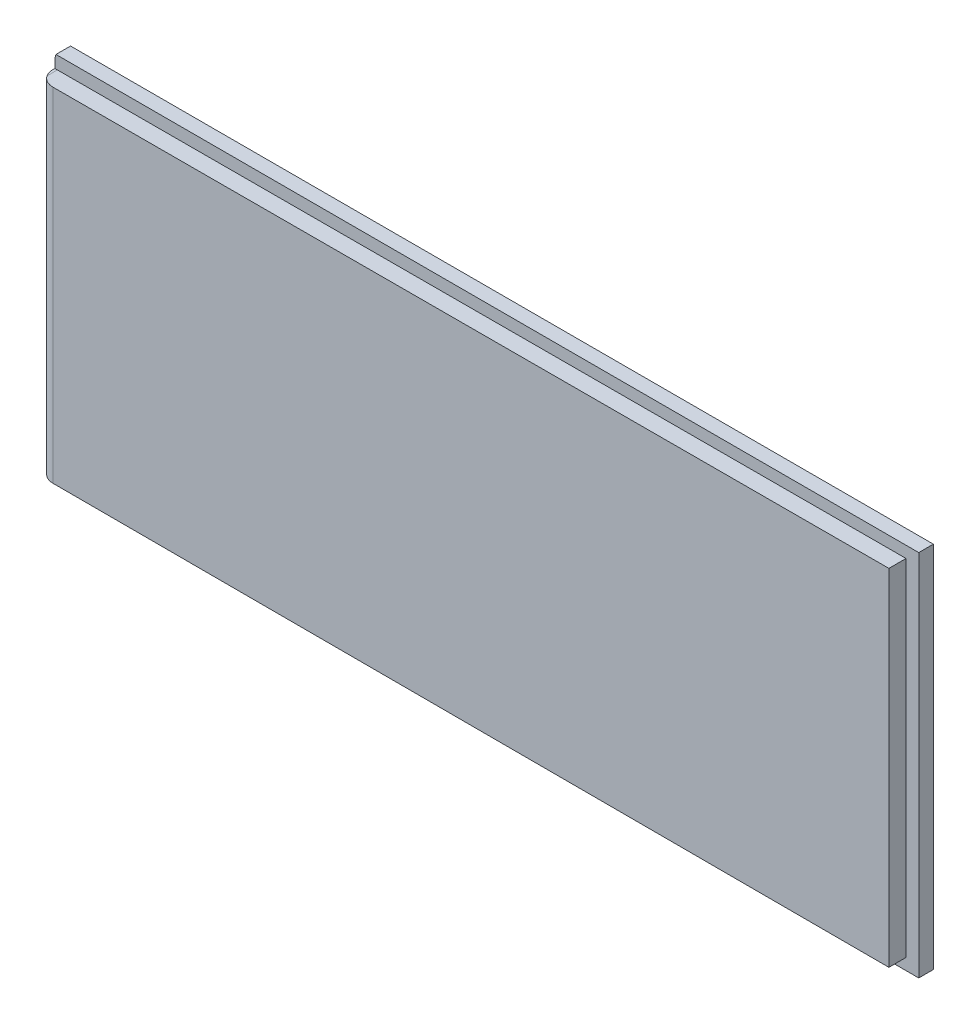
SolidWorks part; units mm, degrees
ref_plane "前视基准面" through (0, 0, 0) normal (0, 0, 1) x (1, 0, 0)
ref_plane "上视基准面" through (0, 0, 0) normal (0, 1, 0) x (1, 0, 0)
ref_plane "右视基准面" through (0, 0, 0) normal (1, 0, 0) x (0, 0, -1)
sketch "草图1" plane through (0, 0, -0.6466) normal (0, 0, 1) x (1, 0, 0)
  line L7 (-91.5, 11.1) -> (-91.5, -11.1) construction
  line L8 (-91.3, 11.1) -> (-91.3, -11.1)
  line L9 (-91.3, -11.1) -> (-91.3, -14)
  line L10 (-91.1125, -14.8) -> (-22.7, -14.8)
  line L11 (-22.7, -14.8) -> (-22.7, 14.8)
  line L12 (-74.5, 11.1) -> (-74.5, 14.3)
  line L13 (-74.5, 14.3) -> (-23.3, 14.3)
  line L14 (-22.7, 14.8) -> (-91.1125, 14.8)
  line L15 (-23.3, 14.3) -> (-23.3, -14.3)
  line L16 (-74.5, -14.3) -> (-74.5, -11.1)
  line L17 (-75.5, -10.1) -> (-90.5, -10.1)
  line L18 (-91.5, -11.1) -> (-91.5, -14)
  line L19 (-91.2321, -15) -> (-22.5, -15)
  line L20 (-22.5, -15) -> (-22.5, 15)
  line L21 (-22.5, 15) -> (-91.2321, 15)
  line L22 (-91.5, 14) -> (-91.5, 11.1)
  line L23 (-90.5, 10.1) -> (-75.5, 10.1)
  line L30 (-91.5, -11.1) -> (-91.5, -14) construction
  line L31 (-91.2321, -15) -> (-22.5, -15) construction
  line L32 (-22.5, -15) -> (-22.5, 15) construction
  line L33 (-22.5, 15) -> (-91.2321, 15) construction
  line L34 (-91.5, 14) -> (-91.5, 11.1) construction
  line L36 (-91.3, 14) -> (-91.3, 11.1)
  line L55 (-23.3, -14.3) -> (-74.5, -14.3)
  arc A2 (-91.3, -14) -> (-91.1125, -14.8) centre (-89.5, -14) ccw
  arc A3 (-91.1125, 14.8) -> (-91.3, 14) centre (-89.5, 14) ccw
  arc A4 (-75.5, 10.1) -> (-74.5, 11.1) centre (-75.5, 11.1) ccw
  arc A5 (-74.5, -11.1) -> (-75.5, -10.1) centre (-75.5, -11.1) ccw
  arc A6 (-91.5, -14) -> (-91.2321, -15) centre (-89.5, -14) ccw
  arc A7 (-91.2321, 15) -> (-91.5, 14) centre (-89.5, 14) ccw
  arc A10 (-91.5, -14) -> (-91.2321, -15) centre (-89.5, -14) ccw construction
  arc A11 (-91.2321, 15) -> (-91.5, 14) centre (-89.5, 14) ccw construction
  arc A22 (-90.5, -10.1) -> (-91.5, -11.1) centre (-90.5, -11.1) ccw
  arc A24 (-91.5, 11.1) -> (-90.5, 10.1) centre (-90.5, 11.1) ccw
  dimension "D1" = 0
  dimension "D2" = 0.2
extrude "凸台-拉伸1" add sketch "草图1" along normal blind 1.15
sketch "草图2" plane through (0, 0, 0.5034) normal (0, 0, 1) x (1, 0, 0)
  line L4 (-91.2, 14) -> (-91.2, -14)
  line L6 (-91.2, 14) -> (-91.2, -14)
  line L8 (-91.0492, -14.7) -> (-22.8, -14.7)
  line L10 (-91.0492, -14.7) -> (-22.8, -14.7)
  line L16 (-91.4, 14) -> (-91.4, -14)
  line L18 (-91.4, 14) -> (-91.4, -14)
  line L20 (-91.1733, -14.9) -> (-22.6, -14.9)
  line L22 (-91.1733, -14.9) -> (-22.6, -14.9)
  line L24 (-22.8, -14.7) -> (-22.8, 14.7)
  line L25 (-22.8, -14.7) -> (-22.8, 14.7)
  line L26 (-22.8, 14.7) -> (-91.0492, 14.7)
  line L27 (-22.8, 14.7) -> (-91.0492, 14.7)
  line L28 (-22.6, -14.9) -> (-22.6, 14.9)
  line L29 (-22.6, -14.9) -> (-22.6, 14.9)
  line L30 (-22.6, 14.9) -> (-91.1733, 14.9)
  line L31 (-22.6, 14.9) -> (-91.1733, 14.9)
  arc A2 (-91.2, -14) -> (-91.0492, -14.7) centre (-89.5, -14) ccw
  arc A4 (-91.2, -14) -> (-91.0492, -14.7) centre (-89.5, -14) ccw
  arc A8 (-91.4, -14) -> (-91.1733, -14.9) centre (-89.5, -14) ccw
  arc A10 (-91.4, -14) -> (-91.1733, -14.9) centre (-89.5, -14) ccw
  arc A12 (-91.0492, 14.7) -> (-91.2, 14) centre (-89.5, 14) ccw
  arc A13 (-91.0492, 14.7) -> (-91.2, 14) centre (-89.5, 14) ccw
  arc A14 (-91.1733, 14.9) -> (-91.4, 14) centre (-89.5, 14) ccw
  arc A15 (-91.1733, 14.9) -> (-91.4, 14) centre (-89.5, 14) ccw
  dimension "D1" = 0.1
  dimension "D2" = 0.1
extrude "切除-拉伸1" cut sketch "草图2" against normal blind 1.23
sketch "草图4" plane through (0, 0, 0.5034) normal (0, 0, 1) x (1, 0, 0)
  line L0 (-91.5, 14) -> (-23.5, 14.1) construction
  line L1 (-23.5, 14.1) -> (-23.5, -14.1) construction
  line L2 (-23.5, -14.1) -> (-91.5, -14) construction
  line L3 (-91.5, -14) -> (-91.5, 14) construction
  line L8 (-91.2, 13.7004) -> (-23.8, 13.7996)
  line L9 (-23.8, 13.7996) -> (-23.8, -13.7996)
  line L10 (-23.8, -13.7996) -> (-91.2, -13.7004)
  line L11 (-91.2, -13.7004) -> (-91.2, 13.7004)
  dimension "D1" = 0.3
extrude "凸台-拉伸2" add sketch "草图4" along normal up to surface (1.35 mm away)
sketch "草图5" plane through (0, 0, -0.6466) normal (0, 0, -1) x (-1, 0, 0)
  line L4 (90.9142, 14.5) -> (23, 14.5)
  line L5 (90.9142, 14.5) -> (23, 14.5)
  line L6 (23, 14.5) -> (23, -14.5)
  line L7 (23, 14.5) -> (23, -14.5)
  line L8 (23, -14.5) -> (90.9142, -14.5)
  line L9 (23, -14.5) -> (90.9142, -14.5)
  line L10 (91, -14) -> (91, 14)
  line L11 (91, -14) -> (91, 14)
  line L16 (91.0492, 14.7) -> (22.8, 14.7)
  line L17 (91.0492, 14.7) -> (22.8, 14.7)
  line L18 (22.8, 14.7) -> (22.8, -14.7)
  line L19 (22.8, 14.7) -> (22.8, -14.7)
  line L24 (22.8, -14.7) -> (91.0492, -14.7)
  line L25 (22.8, -14.7) -> (91.0492, -14.7)
  line L26 (91.2, -14) -> (91.2, 14)
  line L27 (91.2, -14) -> (91.2, 14)
  arc A2 (91, 14) -> (90.9142, 14.5) centre (89.5, 14) ccw
  arc A3 (91, 14) -> (90.9142, 14.5) centre (89.5, 14) ccw
  arc A4 (90.9142, -14.5) -> (91, -14) centre (89.5, -14) ccw
  arc A5 (90.9142, -14.5) -> (91, -14) centre (89.5, -14) ccw
  arc A8 (91.2, 14) -> (91.0492, 14.7) centre (89.5, 14) ccw
  arc A9 (91.2, 14) -> (91.0492, 14.7) centre (89.5, 14) ccw
  arc A12 (91.0492, -14.7) -> (91.2, -14) centre (89.5, -14) ccw
  arc A13 (91.0492, -14.7) -> (91.2, -14) centre (89.5, -14) ccw
  dimension "D1" = 0.2
  dimension "D2" = 0
extrude "切除-拉伸2" cut sketch "草图5" against normal blind 10
sketch "草图6" plane through (0, 0, 1.8534) normal (0, 0, 1) x (1, 0, 0)
  line L16 (-24, 13.5993) -> (-90.8, 13.501)
  line L17 (-90.8, 13.501) -> (-90.8, -13.501)
  line L18 (-90.8, -13.501) -> (-24, -13.5993)
  line L19 (-24, -13.5993) -> (-24, 13.5993)
  line L25 (-24, 13.5993) -> (-90.8, 13.501)
  line L28 (-90.8, -13.501) -> (-24, -13.5993)
  line L29 (-24, -13.5993) -> (-24, 13.5993)
  line L30 (-90.8, 13.501) -> (-91, 13.501)
  line L31 (-90.8, -13.501) -> (-91, -13.501)
  line L32 (-91, -13.501) -> (-91, -13.7007)
  line L34 (-23.8, 13.7996) -> (-91, 13.7007)
  line L35 (-91, 13.7007) -> (-91, -13.7007)
  line L36 (-91, -13.7007) -> (-23.8, -13.7996)
  line L37 (-23.8, -13.7996) -> (-23.8, 13.7996)
  line L38 (-23.8, 13.7996) -> (-91, 13.7007)
  line L39 (-91, 13.7007) -> (-91, 13.501)
  line L40 (-91, -13.7007) -> (-23.8, -13.7996)
  line L41 (-23.8, -13.7996) -> (-23.8, 13.7996)
  dimension "D1" = 0.2
  dimension "D2" = 0
extrude "切除-拉伸3" cut sketch "草图6" against normal up to surface (1.35 mm away) up to face at (-63.9471, 0, 0.5034)
fillet "圆角1" radius 1.2 1 edges at (-91, 0, 1.8534)
